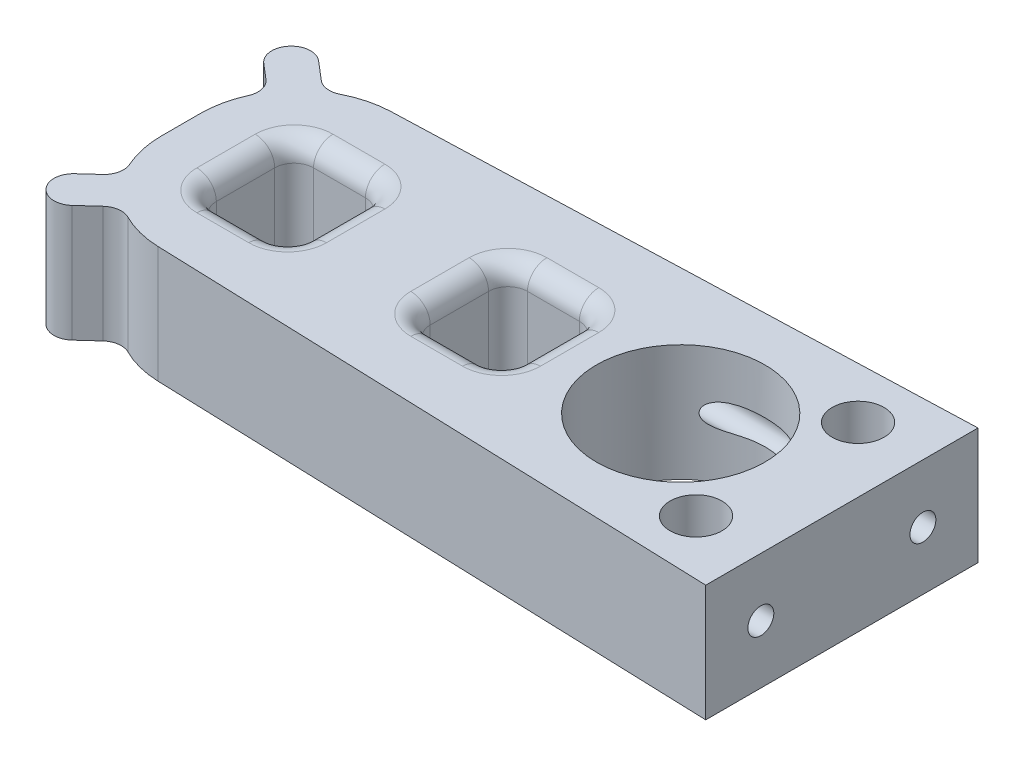
SolidWorks part; units mm, degrees
material "PE High Density"
ref_plane "Front Plane" through (0, 0, 0) normal (0, 0, 1) x (1, 0, 0)
ref_plane "Top Plane" through (0, 0, 0) normal (0, 1, 0) x (1, 0, 0)
ref_plane "Right Plane" through (0, 0, 0) normal (1, 0, 0) x (0, 0, -1)
sketch "Sketch1" plane through (0, 0, 0) normal (0, 1, 0) x (1, 0, 0)
  line L0 (-17, 17.5) -> (85, 21)
  line L1 (85, 21) -> (85, 9.1072)
  line L2 (40, 7.5) -> (26, 7.5)
  line L3 (26, 7.5) -> (26, -7.5)
  line L4 (26, -7.5) -> (40, -7.5)
  line L5 (85, 9.1072) -> (85, -21)
  line L6 (85, -21) -> (-17, -17.5)
  line L7 (-17, -17.5) -> (-17, 17.5)
  line L8 (-7, 7.5) -> (7, 7.5)
  line L9 (-7, 7.5) -> (-7, -7.5)
  line L10 (7, 7.5) -> (7, -7.5)
  line L11 (-7, -7.5) -> (7, -7.5)
  line L12 (-7, 7.5) -> (7, -7.5) construction
  line L13 (7, 7.5) -> (-7, -7.5) construction
  line L14 (-17, 7.5) -> (-7, 7.5) construction
  line L15 (7, 0) -> (26, 0) construction
  line L16 (40, -7.5) -> (40, 7.5)
  line L17 (-17, 0) -> (-7, 0) construction
  point P9 (0, 0)
  dimension "D6" = 102
  dimension "D1" = 15
  dimension "D2" = 35
  dimension "D3" = 14
  dimension "D4" = 19
  dimension "D5" = 14
  dimension "D7" = 42
  dimension "D8" = 10
extrude "Boss-Extrude1" add sketch "Sketch1" along normal blind 18
fillet "Fillet1" radius 15 2 edges at (-17, 9, -17.5) (-17, 9, 17.5)
fillet "Fillet2" radius 3 24 edges at (0, 18, -7.5) (33, 0, -7.5) (26, 0, 0) (33, 0, 7.5) (33, 18, -7.5) (26, 18, 0) (33, 18, 7.5) (-7, 0, 0) (0, 0, 7.5) (0, 0, -7.5) (7, 0, 0) (-7, 18, 0) (0, 18, 7.5) (7, 18, 0) (7, 9, -7.5) (26, 9, 7.5) (26, 9, -7.5) (7, 9, 7.5) (-7, 9, 7.5) (-7, 9, -7.5) (40, 9, -7.5) (40, 18, 0) (40, 9, 7.5) (40, 0, 0)
sketch "Sketch2" plane through (85, 0, 0) normal (1, 0, 0) x (0, 0, -1)
  line L0 (0, 18) -> (-25, 0) construction
  line L1 (-21, 18) -> (21, 18) construction
  line L2 (-21, 0) -> (21, 0) construction
  line L3 (-12.5, 9) -> (12.5, 9) construction
  line L4 (-21, 18) -> (21, 18) construction
  line L5 (13.2226, 18) -> (11.7774, 0) construction
  line L6 (-21, 0) -> (21, 0) construction
  line L8 (0, 0) -> (0, 9) construction
  circle A0 centre (-12.5, 9) radius 2
  circle A1 centre (12.5, 9) radius 2
  dimension "D2" = 4
  dimension "D1" = 25
extrude "Cut-Extrude1" cut sketch "Sketch2" against normal blind 50
sketch "Sketch3" plane through (0, 18, 0) normal (0, 1, 0) x (1, 0, 0)
  line L0 (75, -12.5) -> (85, -12.5) construction
  line L1 (85, -21) -> (85, 21) construction
  line L2 (85, 10.5) -> (85, 14.5) construction
  line L3 (75, 12.5) -> (85, 12.5) construction
  line L4 (85, -21) -> (85, 21) construction
  line L5 (85, -14.5) -> (85, -10.5) construction
  line L6 (7, -4.5) -> (7, 4.5) construction
  line L7 (0, 0) -> (16.5, 0) construction
  line L8 (26, 4.5) -> (26, -4.5) construction
  line L9 (40, -4.5) -> (40, 4.5) construction
  line L10 (85, 21) -> (-2.5144, 17.9971) construction
  line L11 (-2.5144, -17.9971) -> (85, -21) construction
  circle A0 centre (75, -12.5) radius 4
  circle A1 centre (75, 12.5) radius 4
  circle A2 centre (75, 12.5) radius 8.1521 construction
  circle A4 centre (60.1349, 0) radius 13
  circle A6 centre (16.5, 0) radius 9.5 construction
  circle A7 centre (60.1349, 0) radius 20.1349 construction
  dimension "D1" = 8
  dimension "D4" = 26
  dimension "D3" = 10
extrude "Cut-Extrude2" cut sketch "Sketch3" against normal blind 15
sketch "Sketch4" plane through (0, 3, 0) normal (0, 1, 0) x (1, 0, 0)
  circle A1 centre (60.1349, 0) radius 13
  circle A2 centre (60.1349, 0) radius 13
  dimension "D1" = 0
extrude "Cut-Extrude3" cut sketch "Sketch4" against normal blind 17
sketch "Sketch5" plane through (0, 18, 0) normal (0, 1, 0) x (1, 0, 0)
  line L0 (-16.6207, -16.9165) -> (-12.7869, -13.429) construction
  line L1 (-18.6395, -14.6973) -> (-14.8056, -11.2098)
  line L2 (-14.602, -19.1357) -> (-10.7682, -15.6482)
  line L3 (-16.8707, 16.9178) -> (-12.7869, 13.429) construction
  line L4 (-14.9221, 19.1988) -> (-10.8383, 15.71)
  line L5 (-18.8194, 14.6368) -> (-14.7356, 11.148)
  arc A0 (-17, -3.0059) -> (-2.5144, -17.9971) centre (-2, -3.0059) ccw construction
  arc A1 (-18.6395, -14.6973) -> (-14.602, -19.1357) centre (-16.6207, -16.9165) ccw
  arc A2 (-10.7682, -15.6482) -> (-14.8056, -11.2098) centre (-12.7869, -13.429) ccw
  arc A3 (-2.5144, 17.9971) -> (-17, 3.0059) centre (-2, 3.0059) ccw construction
  arc A4 (-14.9221, 19.1988) -> (-18.8194, 14.6368) centre (-16.8707, 16.9178) ccw
  arc A5 (-14.7356, 11.148) -> (-10.8383, 15.71) centre (-12.7869, 13.429) ccw
  point P5 (-14.7038, -15.1728)
  point P11 (-14.8288, 15.1734)
  dimension "D1" = 3
extrude "Boss-Extrude2" add sketch "Sketch5" against normal blind 18
fillet "Fillet3" radius 3 4 edges at (-10.497, 9, -15.3671) (-14.6454, 9, -11.074) (-14.6454, 9, 11.074) (-10.497, 9, 15.3671)
